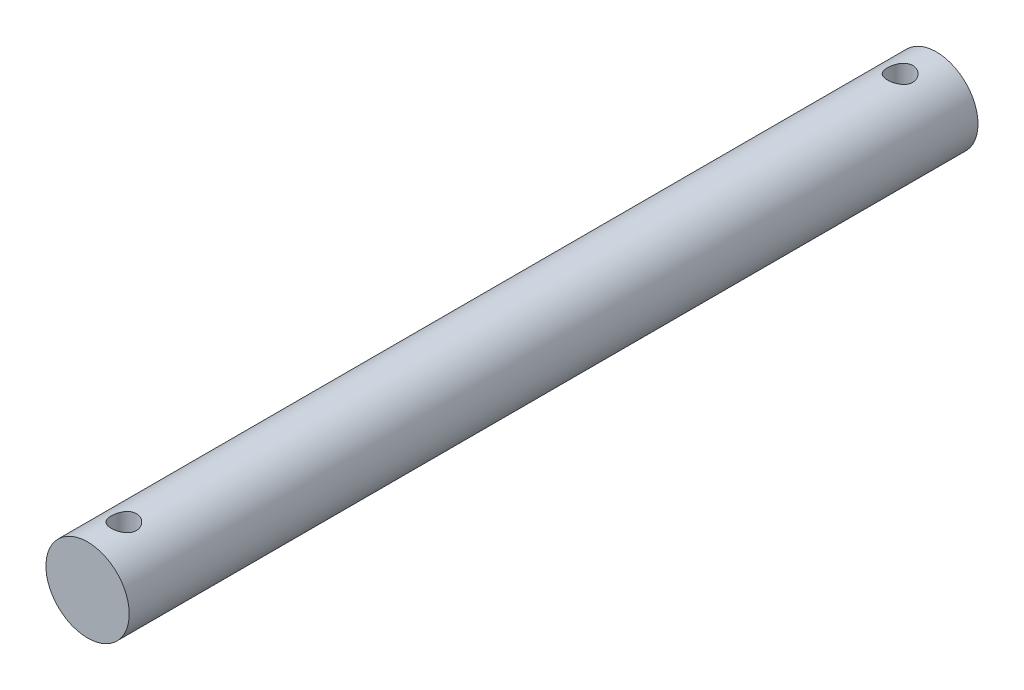
SolidWorks part; units mm, degrees
ref_plane "Front Plane" through (0, 0, 0) normal (0, 0, 1) x (1, 0, 0)
ref_plane "Top Plane" through (0, 0, 0) normal (0, 1, 0) x (1, 0, 0)
ref_plane "Right Plane" through (0, 0, 0) normal (1, 0, 0) x (0, 0, -1)
sketch "Sketch3" plane through (0, 0, 0) normal (0, 0, 1) x (1, 0, 0)
  circle A0 centre (0, 0) radius 5.75
  dimension "D1" = 11.5
extrude "Boss-Extrude1" add sketch "Sketch3" along normal blind 117.15
sketch "Sketch4" plane through (0, 0, 0) normal (0, 1, 0) x (1, 0, 0)
  line L0 (0, -5) -> (0, 0) construction
  circle A0 centre (0, -5) radius 1.75
  dimension "D2" = 3.5
  dimension "D1" = 5
ref_plane "Plane1" through (0, 0, 58.575) normal (0, 0, -1) x (-1, 0, 0)
extrude "Cut-Extrude2" cut sketch "Sketch4" along normal mid plane 30
sketch "Sketch5" plane through (0, 0, 0) normal (0, 1, 0) x (0, 0, -1)
  line L0 (-117.15, 0) -> (-112.15, 0)
  line L1 (-117.15, 5.75) -> (-117.15, -5.75) construction
  circle A0 centre (-112.15, 0) radius 1.75
  dimension "D2" = 3.5
  dimension "D1" = 5
extrude "Cut-Extrude3" cut sketch "Sketch5" against normal mid plane 26
